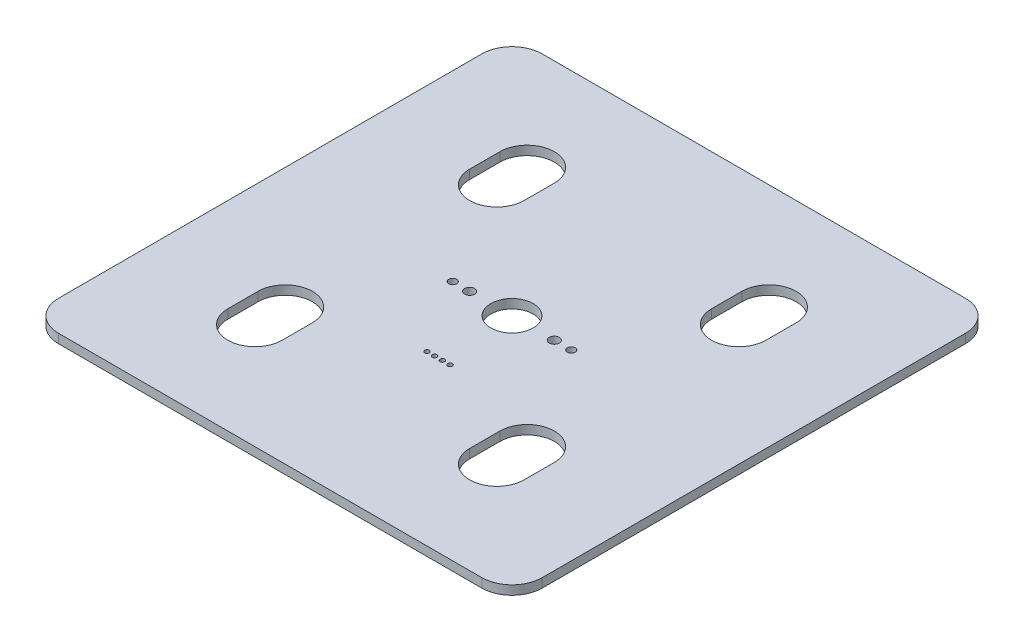
SolidWorks part; units mm, degrees
material "Copper"
ref_plane "Front Plane" through (0, 0, 0) normal (0, 0, 1) x (1, 0, 0)
ref_plane "Top Plane" through (0, 0, 0) normal (0, 1, 0) x (1, 0, 0)
ref_plane "Right Plane" through (0, 0, 0) normal (1, 0, 0) x (0, 0, -1)
sketch "Sketch1" plane through (0, 0, 0) normal (0, 1, 0) x (1, 0, 0)
  line L1 (-40, -40) -> (40, -40)
  line L2 (-40, -40) -> (-40, 40)
  line L3 (-40, 40) -> (40, 40)
  line L4 (40, -40) -> (40, 40)
  line L5 (-40, -40) -> (40, 40) construction
  line L6 (-40, 40) -> (40, -40) construction
  point P0 (0, 0)
  dimension "D1" = 40
extrude "Boss-Extrude1" add sketch "Sketch1" along normal mid plane 1.5
fillet "Fillet1" radius 5 1 edges at (-40, 0, 40)
fillet "Fillet3" radius 5 1 edges at (-40, 0, -40)
fillet "Fillet4" radius 5 1 edges at (40, 0, -40)
fillet "Fillet5" radius 5 1 edges at (40, 0, 40)
sketch "Sketch2" plane through (0, 0.75, 0) normal (0, 1, 0) x (1, 0, 0)
  line L0 (0, 43.5966) -> (0, -43.8986) construction
  line L1 (-44.3014, 0) -> (44.9055, 0) construction
  line L2 (-20, 17.5) -> (-20, 22.5) construction
  line L3 (-24.5, 17.5) -> (-24.5, 22.5)
  line L4 (-15.5, 17.5) -> (-15.5, 22.5)
  line L5 (-20, -17.5) -> (-20, -22.5) construction
  line L6 (-15.5, -17.5) -> (-15.5, -22.5)
  line L7 (-24.5, -17.5) -> (-24.5, -22.5)
  line L8 (20, -17.5) -> (20, -22.5) construction
  line L9 (15.5, -17.5) -> (15.5, -22.5)
  line L10 (24.5, -17.5) -> (24.5, -22.5)
  line L11 (20, 17.5) -> (20, 22.5) construction
  line L12 (24.5, 17.5) -> (24.5, 22.5)
  line L13 (15.5, 17.5) -> (15.5, 22.5)
  arc A0 (-24.5, 17.5) -> (-15.5, 17.5) centre (-20, 17.5) ccw
  arc A1 (-15.5, 22.5) -> (-24.5, 22.5) centre (-20, 22.5) ccw
  arc A2 (-15.5, -17.5) -> (-24.5, -17.5) centre (-20, -17.5) ccw
  arc A3 (-24.5, -22.5) -> (-15.5, -22.5) centre (-20, -22.5) ccw
  arc A4 (15.5, -17.5) -> (24.5, -17.5) centre (20, -17.5) cw
  arc A5 (24.5, -22.5) -> (15.5, -22.5) centre (20, -22.5) cw
  arc A6 (24.5, 17.5) -> (15.5, 17.5) centre (20, 17.5) cw
  arc A7 (15.5, 22.5) -> (24.5, 22.5) centre (20, 22.5) cw
  point P7 (-20, 20)
  point P13 (-20, -20)
  point P22 (20, -20)
  point P29 (20, 20)
  dimension "D4" = 4.5
  dimension "D1" = 20
  dimension "D2" = 20
  dimension "D3" = 20
  dimension "D5" = 5
extrude "Cut-Extrude1" cut sketch "Sketch2" against normal through all both and the other way through all
sketch "Sketch3" plane through (0, 0.75, 0) normal (0, 1, 0) x (1, 0, 0)
  circle A0 centre (0, 0) radius 3.5
  dimension "D1" = 7
extrude "Cut-Extrude2" cut sketch "Sketch3" against normal through all both and the other way through all
sketch "Sketch4" plane through (0, 0.75, 0) normal (0, 1, 0) x (1, 0, 0)
  line L0 (-13.5506, -12.15) -> (0, -12.15) construction
  line L1 (0, 0) -> (0, -12.15) construction
  line L2 (0, 0) -> (-13.5506, 0) construction
  circle A2 centre (-0.635, -12.15) radius 0.38
  circle A3 centre (-1.905, -12.15) radius 0.38
  circle A5 centre (-9.8, 0) radius 0.65
  circle A6 centre (-7, 0) radius 0.825
  circle A7 centre (7, 0) radius 0.825
  circle A8 centre (9.8, 0) radius 0.65
  circle A9 centre (0.635, -12.15) radius 0.38
  circle A10 centre (1.905, -12.15) radius 0.38
  dimension "D4" = 0.76
  dimension "D7" = 1.3
  dimension "D8" = 1.65
  dimension "D1" = 0.635
  dimension "D2" = 7
  dimension "D3" = 9.8
  dimension "D5" = 1.27
  dimension "D6" = 12.15
extrude "Cut-Extrude3" cut sketch "Sketch4" against normal through all both and the other way through all
